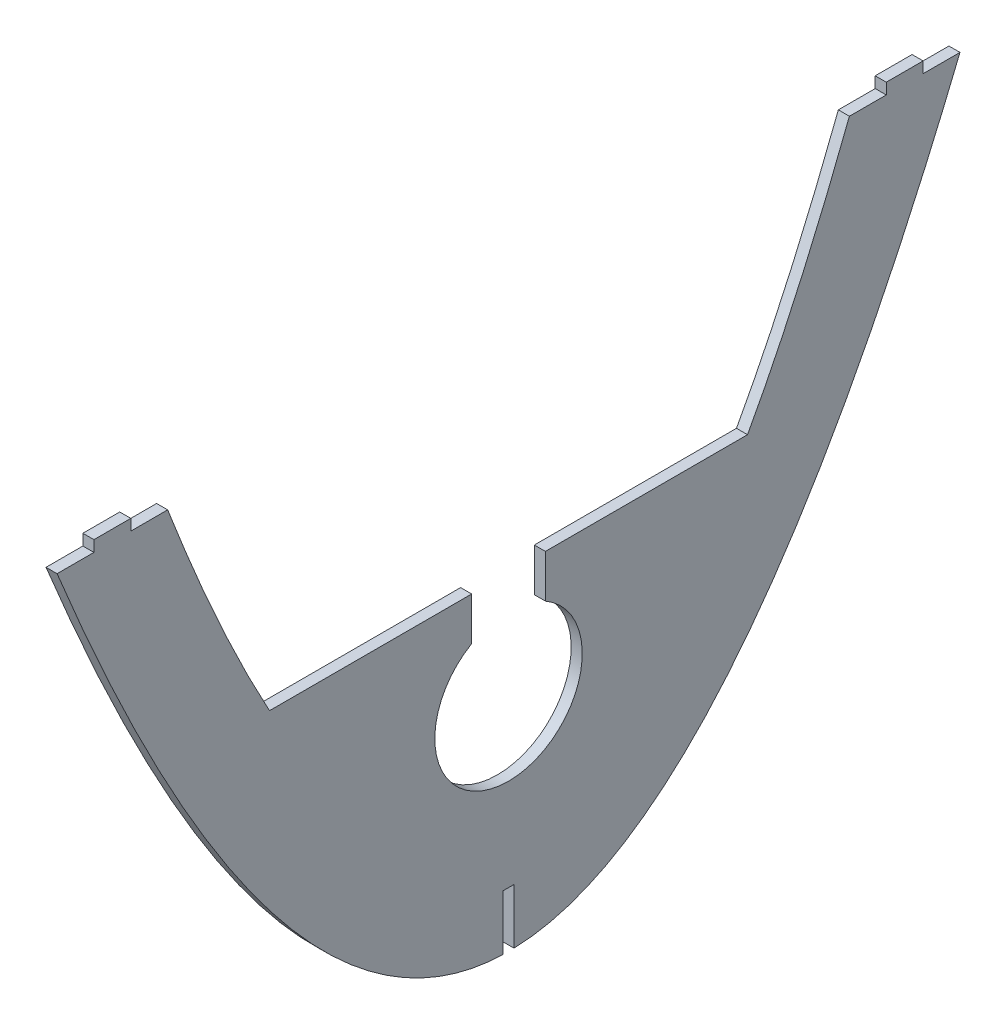
SolidWorks part; units mm, degrees
ref_plane "前视基准面" through (0, 0, 0) normal (0, 0, 1) x (1, 0, 0)
ref_plane "上视基准面" through (0, 0, 0) normal (0, 1, 0) x (1, 0, 0)
ref_plane "右视基准面" through (0, 0, 0) normal (1, 0, 0) x (0, 0, -1)
sketch "草图1" plane through (0, 0, 0) normal (1, 0, 0) x (0, 0, -1)
  line L0 (-122.475, 150.0013) -> (-92.4755, 150.0013)
  line L1 (92.4755, 150.0013) -> (122.475, 150.0013)
  spline S0 degree 2 poles (-137.0837, 187.9194) (0, -187.9194) (137.0837, 187.9194) knots 0 0 0 1 1 1 construction
  spline S1 degree 2 poles (-122.475, 150.0013) (0, -150.0013) (122.475, 150.0013) knots 0.053284 0.053284 0.053284 0.946716 0.946716 0.946716
  spline S2 degree 2 poles (-136.0018, 289.5504) (0, -229.5504) (136.0018, 289.5504) knots 0 0 0 1 1 1 construction
  spline S3 degree 2 poles (-92.4755, 150.0013) (0, -90.0013) (92.4755, 150.0013) knots 0.160021 0.160021 0.160021 0.839979 0.839979 0.839979
extrude "凸台-拉伸1" add sketch "草图1" along normal blind 3
sketch "草图3" plane through (0, 150.0013, 0) normal (0, 1, 0) x (1, 0, 0)
  line L0 (3, 122.475) -> (0, 92.4755)
  line L1 (0, -92.4755) -> (3, -122.475)
  line L2 (3, -92.4755) -> (3, -122.475) construction
  line L3 (0, -112.4752) -> (3, -112.4752)
  line L4 (0, -112.4752) -> (0, -102.4752)
  line L5 (0, -102.4752) -> (3, -102.4752)
  line L6 (3, -112.4752) -> (3, -102.4752)
  line L7 (0, -112.4752) -> (3, -102.4752) construction
  line L8 (0, -102.4752) -> (3, -112.4752) construction
  line L9 (0, 122.475) -> (0, 92.4755) construction
  line L10 (3, 102.4752) -> (0, 102.4752)
  line L11 (3, 102.4752) -> (3, 112.4752)
  line L12 (3, 112.4752) -> (0, 112.4752)
  line L13 (0, 102.4752) -> (0, 112.4752)
  line L14 (3, 102.4752) -> (0, 112.4752) construction
  line L15 (3, 112.4752) -> (0, 102.4752) construction
  point P8 (1.5, -107.4752)
  point P15 (1.5, 107.4752)
  line M2 (0, 122.475) -> (0, 92.4755)
  line M4 (3, 92.4755) -> (3, 122.475)
extrude "凸台-拉伸2" add sketch "草图3" along normal blind 3 contours L3 L6 L5 L1 | L5 L4 L3 L1 | L0 L12 L10 M2 | L12 L0 L10 M4
sketch "草图4" plane through (3, 0, 0) normal (1, 0, 0) x (0, 0, -1)
  line L0 (-10, 89) -> (-64.8425, 89)
  line L3 (64.8425, 89) -> (10, 89)
  line L5 (-10, 77.3205) -> (-10, 89)
  line L9 (10, 77.3205) -> (10, 89)
  arc A0 (-10, 77.3205) -> (10, 77.3205) centre (0, 60) ccw
  parabola Q0 (92.4755, 150.0013) -> (-92.4755, 150.0013) focus (0, 47.8159) apex (0, 30) construction
  parabola Q1 (92.4755, 150.0013) -> (-92.4755, 150.0013) focus (0, 47.8159) apex (0, 30) construction
  parabola Q2 (92.4755, 150.0013) -> (-92.4755, 150.0013) focus (0, 47.8159) apex (0, 30) construction
  parabola Q3 (64.8425, 89) -> (-64.8425, 89) focus (0, 47.8159) apex (0, 30)
extrude "凸台-拉伸3" add sketch "草图4" against normal blind 3
sketch "草图5" plane through (0, 0, 0) normal (-1, 0, 0) x (0, 0, 1)
  line L0 (1.5, 15.0078) -> (1.5, 30.0156) construction
  line L1 (1.5, 15.0078) -> (1.5, 30.0156)
  line L2 (-1.5, 15.0078) -> (-1.5, 30.0156) construction
  line L3 (-1.5, 15.0078) -> (-1.5, 30.0156)
  line L5 (-1.5, 15.0078) -> (1.5, 15.0078)
  line L6 (-1.5, 15.0078) -> (-1.5, -3.1297)
  line L7 (-1.5, -3.1297) -> (1.5, -3.1297)
  line L8 (1.5, 15.0078) -> (1.5, -3.1297)
  spline M7 degree 2 poles (-122.475, 150.0013) (0, -150.0013) (122.475, 150.0013) knots 0.053284 0.053284 0.053284 0.946716 0.946716 0.946716
extrude "切除-拉伸1" cut sketch "草图5" against normal through all contours L8 L5 L6 M7
